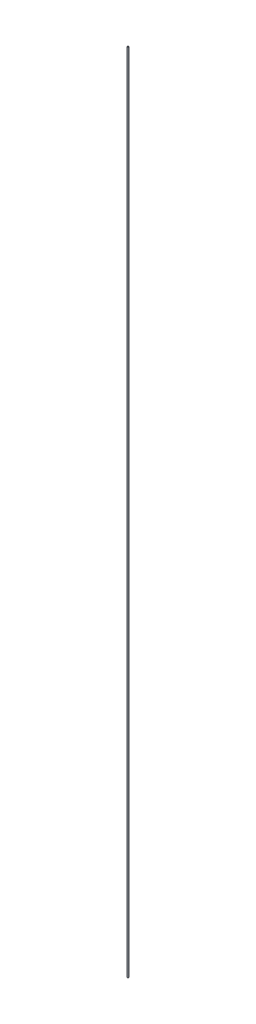
SolidWorks part; units mm, degrees
ref_plane "Front Plane" through (0, 0, 0) normal (0, 0, 1) x (1, 0, 0)
ref_plane "Top Plane" through (0, 0, 0) normal (0, 1, 0) x (1, 0, 0)
ref_plane "Right Plane" through (0, 0, 0) normal (1, 0, 0) x (0, 0, -1)
sketch "Sketch1" plane through (0, 0, 0) normal (0, 0, 1) x (1, 0, 0)
  line L0 (0, 0) -> (0, 8507.984)
  dimension "D1" = 8507.984
sweep "Sweep1" add path "Sketch1" circular profile diameter 12.7 parameters "D3"=12.7
